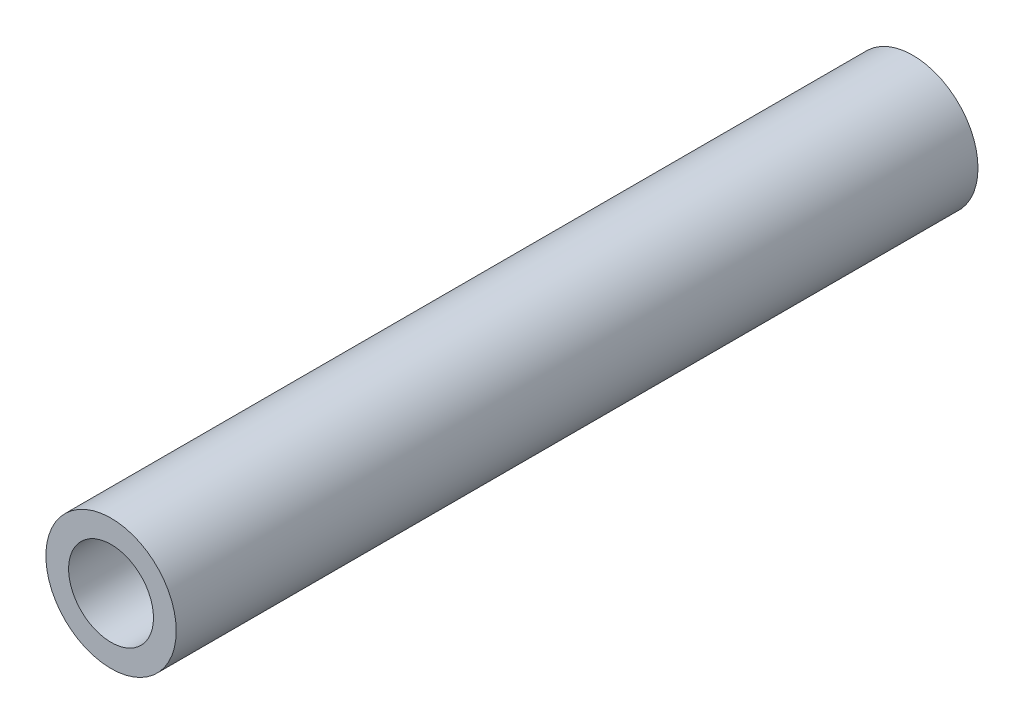
SolidWorks part; units mm, degrees
ref_plane "Front Plane" through (0, 0, 0) normal (0, 0, 1) x (1, 0, 0)
ref_plane "Top Plane" through (0, 0, 0) normal (0, 1, 0) x (1, 0, 0)
ref_plane "Right Plane" through (0, 0, 0) normal (1, 0, 0) x (0, 0, -1)
sketch "Sketch1" plane through (0, 0, 0) normal (0, 0, 1) x (1, 0, 0)
  circle A0 centre (-8.5, 74.4) radius 2.8
  circle A1 centre (-8.5, 74.4) radius 4.3
  dimension "D1" = 5.6
  dimension "D2" = 8.6
extrude "Boss-Extrude1" add sketch "Sketch1" along normal blind 52.9
